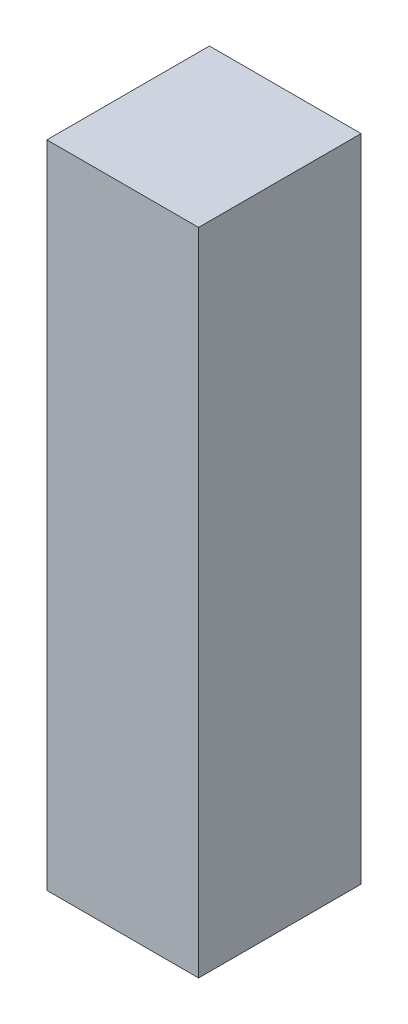
SolidWorks part; units mm, degrees
ref_plane "Спереди" through (0, 0, 0) normal (0, 0, 1) x (1, 0, 0)
ref_plane "Сверху" through (0, 0, 0) normal (0, 1, 0) x (1, 0, 0)
ref_plane "Справа" through (0, 0, 0) normal (1, 0, 0) x (0, 0, -1)
sketch "Эскиз1" plane through (0, 0, 0) normal (0, 1, 0) x (1, 0, 0)
  line L1 (0, 0) -> (7, 0)
  line L2 (0, 0) -> (0, -7.5)
  line L3 (0, -7.5) -> (7, -7.5)
  line L4 (7, 0) -> (7, -7.5)
extrude "Вытянуть1" add sketch "Эскиз1" along normal blind 30
